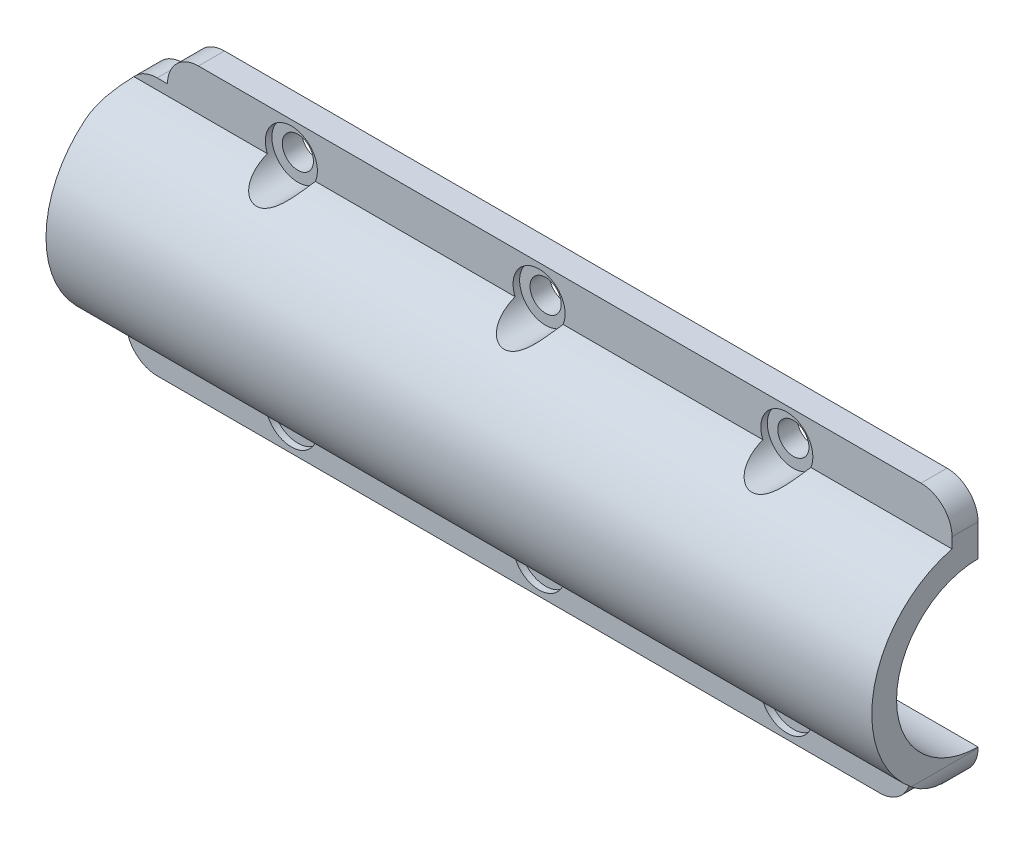
SolidWorks part; units mm, degrees
material "ABS"
ref_plane "X-Y Datum" through (0, 0, 0) normal (0, 0, 1) x (1, 0, 0)
ref_plane "X-Z Datum" through (0, 0, 0) normal (0, 1, 0) x (1, 0, 0)
ref_plane "Y-Z Datum" through (0, 0, 0) normal (1, 0, 0) x (0, 0, -1)
sketch "Sketch1" plane through (0, 0, 0) normal (1, 0, 0) x (0, 0, -1)
  line L0 (0, 22.225) -> (0, 17.4625) construction
  line L1 (-4, 22.225) -> (-4, 15.8396)
  line L2 (0, -22.225) -> (-4, -22.225)
  line L3 (-4, 11.8711) -> (-4, 11.3422)
  line L4 (-4, -15.8396) -> (-4, -22.225)
  line L5 (0, 12.5269) -> (0, 12.0269)
  line L6 (0, -12.5269) -> (0, -12.0269)
  line L15 (16.3195, -17.4625) -> (16.3195, 17.4625)
  line L17 (0, -12.5269) -> (0, -17.4625)
  line L18 (0, 17.4625) -> (0, 12.5269)
  line L27 (10.3195, 22.225) -> (0, 22.225) construction
  line L28 (10.3195, 22.225) -> (-4, 22.225)
  line L29 (0, 22.225) -> (0, 17.4625)
  line L32 (0, -22.225) -> (16.3195, -22.225)
  line L33 (16.3195, 17.4625) -> (0, 17.4625)
  line L36 (0, -17.4625) -> (0, -22.225)
  line L43 (0, -17.4625) -> (16.3195, -17.4625)
  arc A1 (0, -12.5269) -> (0, 12.5269) centre (0, 0) cw
  arc A2 (0, -12.5269) -> (0, 12.5269) centre (0, 0) ccw
  circle A3 centre (0, 0) radius 12.0269
  circle A4 centre (0, 0) radius 12.0269
  circle A5 centre (0, 0) radius 16.3369
  dimension "D5" = 4
  dimension "D2" = 0
extrude "Boss-Extrude1" add sketch "Sketch1" along normal blind 114.3
sketch "Sketch2" plane through (0, 0, 4) normal (0, 0, 1) x (1, 0, 0)
  circle A0 centre (19.05, -17.376) radius 4
  circle A1 centre (57.15, -17.376) radius 4
  circle A2 centre (95.25, -17.376) radius 4
  point P0 (19.05, -17.376)
  point P1 (57.15, -17.376)
  point P3 (95.25, -17.376)
  dimension "D1" = 8
extrude "Cut-Extrude1" cut sketch "Sketch2" against normal blind 1 and the other way blind 6.35
hole_wizard "M4 Clearance Hole1" positions "Sketch7" profile "Sketch6" hole size "M4" standard "ANSI Metric" end condition through all
sketch "Sketch7" plane through (0, 0, 4) normal (0, 0, 1) x (1, 0, 0)
  point P0 (19.05, -17.376)
  point P3 (57.15, -17.376)
  point P6 (95.25, -17.376)
sketch "Sketch6" plane through (19.05, -17.376, 4) normal (1, 0, 0) x (0, -1, 0)
  line L0 (0, 0) -> (0, 4)
  line L1 (0, 4) -> (2.4, 4)
  line L2 (2.4, 4) -> (2.4, 0)
  line L5 (2.4, 0) -> (0, 0)
  line L11 (0, -6.35) -> (0, 107.95) construction
  dimension "Thru Hole Dia." = 4.8
  dimension "Thru Hole Depth" = 4
mirror "Mirror1" about plane through (0, 0, 0) normal (0, 1, 0) of "M4 Clearance Hole1", "Cut-Extrude1"
fillet "Fillet1" radius 4.7625 2 edges at (114.3, -22.225, 2) (0, 22.225, 2)
sketch "Sketch8" plane through (0, 0, 0) normal (-1, 0, 0) x (0, 0, 1)
  line L6 (4, 15.8396) -> (4, 17.4625)
  line L7 (4, 17.4625) -> (0, 17.4625)
  line L8 (0, 17.4625) -> (0, 12.5269)
  line L9 (0, -12.5269) -> (0, -22.225)
  line L10 (0, -22.225) -> (4, -22.225)
  line L11 (4, -22.225) -> (4, -15.8396)
  line L12 (4, 15.8396) -> (4, 17.4625)
  line L13 (4, 17.4625) -> (0, 17.4625)
  line L15 (0, -12.5269) -> (0, -22.225)
  line L16 (0, -22.225) -> (4, -22.225)
  line L17 (4, -22.225) -> (4, -15.8396)
  line L18 (0, 17.4625) -> (0, 12.5269)
  arc A2 (0, -12.5269) -> (0, 12.5269) centre (0, 0) ccw
  arc A3 (4, -15.8396) -> (4, 15.8396) centre (0, 0) ccw
  arc A5 (4, -15.8396) -> (4, 15.8396) centre (0, 0) ccw
  arc A6 (0, -12.5269) -> (0, 12.5269) centre (0, 0) ccw
  dimension "D1" = 0
extrude "Boss-Extrude2" add sketch "Sketch8" along normal blind 6.35 contours L12 L13 L18 A6 L15 L16 L17 A5
sketch "Sketch9" plane through (114.3, 0, 0) normal (1, 0, 0) x (0, 0, -1)
  line L6 (-4, -15.8396) -> (-4, -17.4625)
  line L7 (-4, -17.4625) -> (0, -17.4625)
  line L8 (0, -17.4625) -> (0, -12.5269)
  line L9 (0, 12.5269) -> (0, 22.225)
  line L10 (0, 22.225) -> (-4, 22.225)
  line L11 (-4, 22.225) -> (-4, 15.8396)
  line L12 (-4, -15.8396) -> (-4, -17.4625)
  line L13 (-4, -17.4625) -> (0, -17.4625)
  line L14 (0, -17.4625) -> (0, -12.5269)
  line L16 (0, 22.225) -> (-4, 22.225)
  line L17 (-4, 22.225) -> (-4, 15.8396)
  line L18 (0, 12.5269) -> (0, 22.225)
  arc A2 (0, 12.5269) -> (0, -12.5269) centre (0, 0) ccw
  arc A3 (-4, 15.8396) -> (-4, -15.8396) centre (0, 0) ccw
  arc A5 (-4, 15.8396) -> (-4, -15.8396) centre (0, 0) ccw
  arc A6 (0, 12.5269) -> (0, -12.5269) centre (0, 0) ccw
  dimension "D1" = 0
extrude "Boss-Extrude3" add sketch "Sketch9" along normal blind 6.35
fillet "Fillet2" radius 4.7625 4 edges at (120.65, -17.4625, 2) (120.65, 22.225, 2) (-6.35, 17.4625, 2) (-6.35, -22.225, 2)
